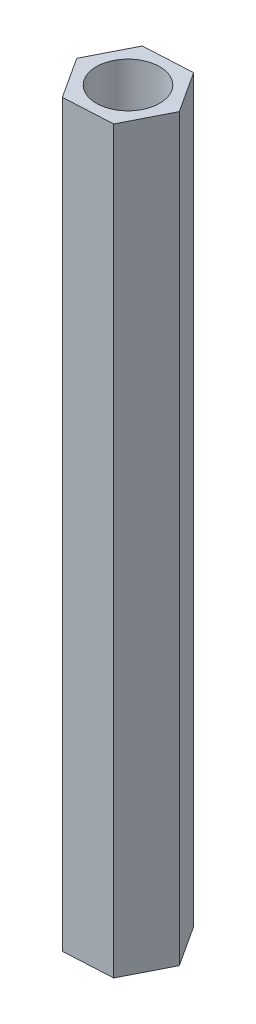
SolidWorks part; units mm, degrees
material "黄铜"
ref_plane "前视基准面" through (0, 0, 0) normal (0, 0, 1) x (1, 0, 0)
ref_plane "上视基准面" through (0, 0, 0) normal (0, 1, 0) x (1, 0, 0)
ref_plane "右视基准面" through (0, 0, 0) normal (1, 0, 0) x (0, 0, -1)
sketch "草图1" plane through (0, 0, 0) normal (0, 1, 0) x (1, 0, 0)
  line L1 (1.0477, 2.0581) -> (-1.2585, 1.9364)
  line L2 (-1.2585, 1.9364) -> (-2.3062, -0.1217)
  line L3 (-2.3062, -0.1217) -> (-1.0477, -2.0581)
  line L4 (-1.0477, -2.0581) -> (1.2585, -1.9364)
  line L5 (1.2585, -1.9364) -> (2.3062, 0.1217)
  line L6 (2.3062, 0.1217) -> (1.0477, 2.0581)
  circle A0 centre (0, 0) radius 1.5
  circle A1 centre (0, 0) radius 2 construction
  dimension "D1" = 3
  dimension "D2" = 4
extrude "凸台-拉伸1" add sketch "草图1" along normal blind 35
